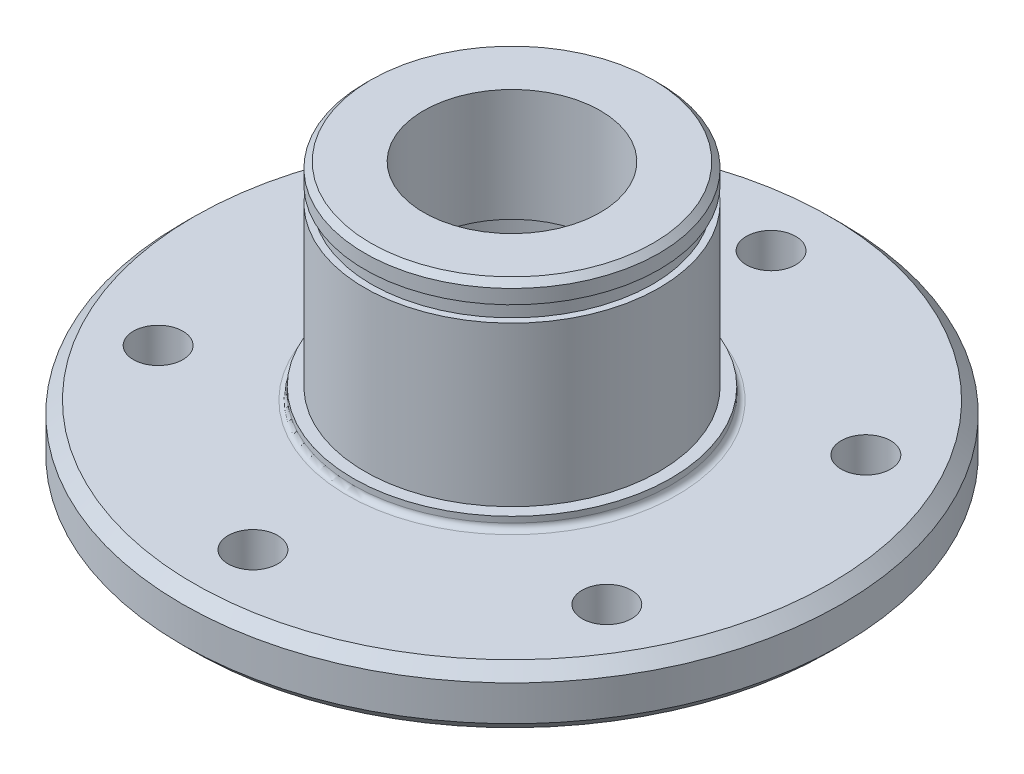
SolidWorks part; units mm, degrees
material "6061-T6 (SS)"
ref_plane "前视基准面" through (0, 0, 0) normal (0, 0, 1) x (1, 0, 0)
ref_plane "上视基准面" through (0, 0, 0) normal (0, 1, 0) x (1, 0, 0)
ref_plane "右视基准面" through (0, 0, 0) normal (1, 0, 0) x (0, 0, -1)
ref_plane "基准面1" through (0, 0, 0) normal (0, 0, -1) x (-1, 0, 0)
sketch "草图1" plane through (0, 0, 0) normal (0, 0, -1) x (-1, 0, 0)
  line L0 (-28, 0) -> (0, 0)
  line L1 (0, 0) -> (0, 22.55)
  line L2 (0, 22.55) -> (-12.5, 22.55)
  line L3 (-12.5, 22.55) -> (-12.5, 20.85)
  line L4 (-12.5, 20.85) -> (-11.95, 20.85)
  line L5 (-11.95, 20.85) -> (-11.95, 19.5)
  line L6 (-11.95, 19.5) -> (-12.5, 19.5)
  line L7 (-12.5, 19.5) -> (-12.5, 6)
  line L10 (-12.5, 6) -> (-13.5, 6)
  line L11 (-13.5, 6) -> (-13.5, 5)
  line L12 (-13.5, 5) -> (-28, 5)
  line L13 (-28, 5) -> (-28, 0)
  line L14 (0, 0) -> (0, 22.55) construction
  point P8 (-12.225, 19.5)
  dimension "D1" = 28
  dimension "D2" = 5
  dimension "D3" = 12.5
  dimension "D4" = 1
  dimension "D5" = 1
  dimension "D6" = 11.95
  dimension "D7" = 14.5
  dimension "D8" = 1.35
  dimension "D9" = 1.7
revolve "旋转1" add sketch "草图1" angle 360 about L14
hole_wizard "M5 螺纹孔1" positions "草图5" profile "草图4" tap size "M5" standard "GB" end condition through all
sketch "草图5" plane through (0, 0, 0) normal (0, -1, 0) x (-1, 0, 0)
  point P0 (0, -22)
  point P1 (-19.0526, -11)
  point P2 (-19.0526, 11)
  point P3 (0, 22)
  point P4 (19.0526, 11)
  point P5 (19.0526, -11)
  dimension "D1" = 22
  dimension "D2" = 22
  dimension "D3" = 22
  dimension "D4" = 22
  dimension "D5" = 22
  dimension "D6" = 22
cosmetic thread "孔螺蚊线1" parameters "D2"=5
cosmetic thread "孔螺蚊线2" parameters "D2"=5
cosmetic thread "孔螺蚊线3" parameters "D2"=5
cosmetic thread "孔螺蚊线4" parameters "D2"=5
cosmetic thread "孔螺蚊线5" parameters "D2"=5
cosmetic thread "孔螺蚊线6" parameters "D2"=5
sketch "草图4" plane through (0, 0, 22) normal (1, 0, 0) x (0, 0, -1)
  line L0 (0, 0) -> (0, 22.55)
  line L1 (0, 22.55) -> (2.1, 22.55)
  line L2 (2.1, 22.55) -> (2.1, 0)
  line L5 (2.1, 0) -> (0, 0)
  line L11 (0, -6.35) -> (0, 107.95) construction
  dimension "通孔螺纹孔钻头直径" = 4.2
  dimension "通孔螺纹孔钻头深度" = 22.55
hole_wizard "M20x1.5 螺纹孔1" positions "草图7" profile "草图6" tap size "M20x1.5" standard "ANSI Metric" end condition through all
sketch "草图7" plane through (0, 0, 0) normal (0, -1, 0) x (-1, 0, 0)
  point P0 (0, 0)
sketch "草图6" plane through (0, 0, 0) normal (1, 0, 0) x (0, 0, -1)
  line L0 (0, 0) -> (0, 22.55)
  line L1 (0, 22.55) -> (7.5, 22.55)
  line L3 (7.5, 22.55) -> (7.5, 13)
  line L4 (7.5, 13) -> (10, 13)
  line L5 (10, 13) -> (10, 0)
  line L7 (10, 0) -> (0, 0)
  line L11 (0, -6.35) -> (0, 107.95) construction
  dimension "通孔螺纹孔钻头直径" = 15
  dimension "通孔螺纹孔钻头深度" = 22.55
  dimension "螺纹线主直径" = 20
  dimension "螺纹线深度" = 13
chamfer "倒角1" distance 0.5 angle 45 1 edges at (-12.5, 22.55, 0)
chamfer "倒角2" distance 1 angle 45 3 edges at (-28, 5, 0) (-28, 0, 0) (0, 0, -10)
fillet "圆角1" radius 0.5 1 edges at (-13.5, 5, 0)
